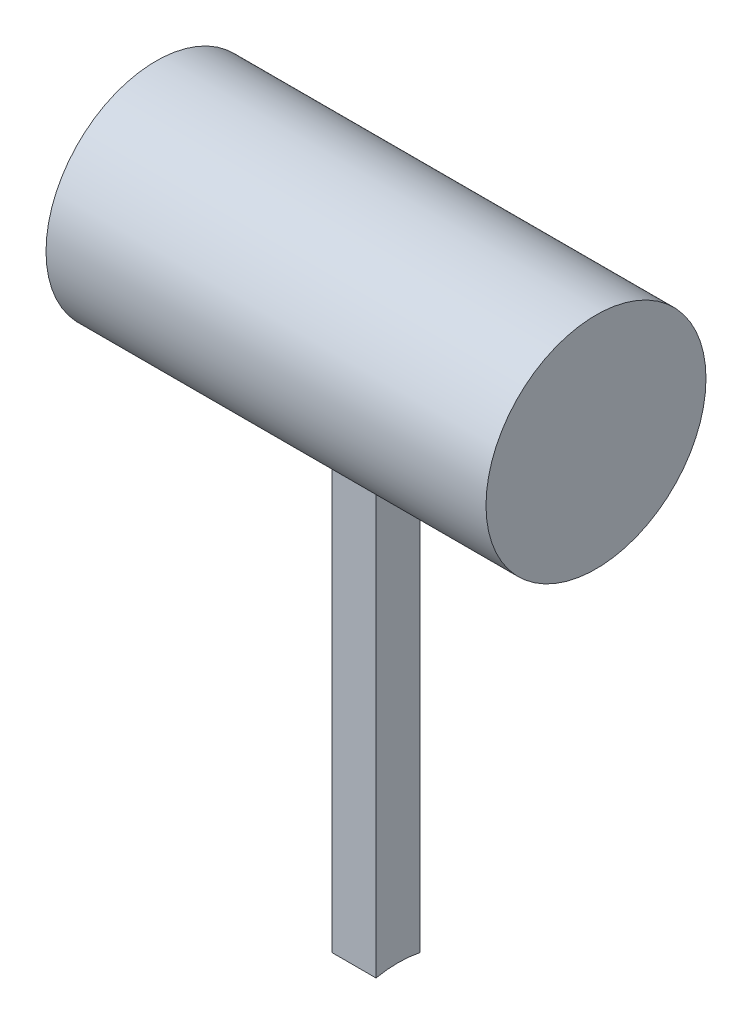
SolidWorks part; units mm, degrees
ref_plane "Front Plane" through (0, 0, 0) normal (0, 0, 1) x (1, 0, 0)
ref_plane "Top Plane" through (0, 0, 0) normal (0, 1, 0) x (1, 0, 0)
ref_plane "Right Plane" through (0, 0, 0) normal (1, 0, 0) x (0, 0, -1)
sketch "Sketch1" plane through (0, 0, 0) normal (1, 0, 0) x (0, 0, -1)
  circle A0 centre (0, 0) radius 5
  dimension "D1" = 10
extrude "Boss-Extrude1" add sketch "Sketch1" along normal mid plane 20
sketch "Sketch2" plane through (0, 0, 0) normal (0, 0, 1) x (1, 0, 0)
  line L1 (-1, 0) -> (1, 0)
  line L2 (-1, 0) -> (-1, -30)
  line L3 (-1, -30) -> (1, -30)
  line L4 (1, 0) -> (1, -30)
  point P4 (0, 0)
  point P5 (0, 0)
  dimension "D1" = 2
  dimension "D2" = 30
extrude "Boss-Extrude2" add sketch "Sketch2" along normal mid plane 2
sketch "Sketch3" plane through (1, 0, 0) normal (1, 0, 0) x (0, 0, -1)
  line L0 (-1, -30) -> (1, -30) construction
  circle A0 centre (0, -30) radius 5
  dimension "D1" = 10
extrude "Cut-Extrude1" cut sketch "Sketch3" against normal through all
